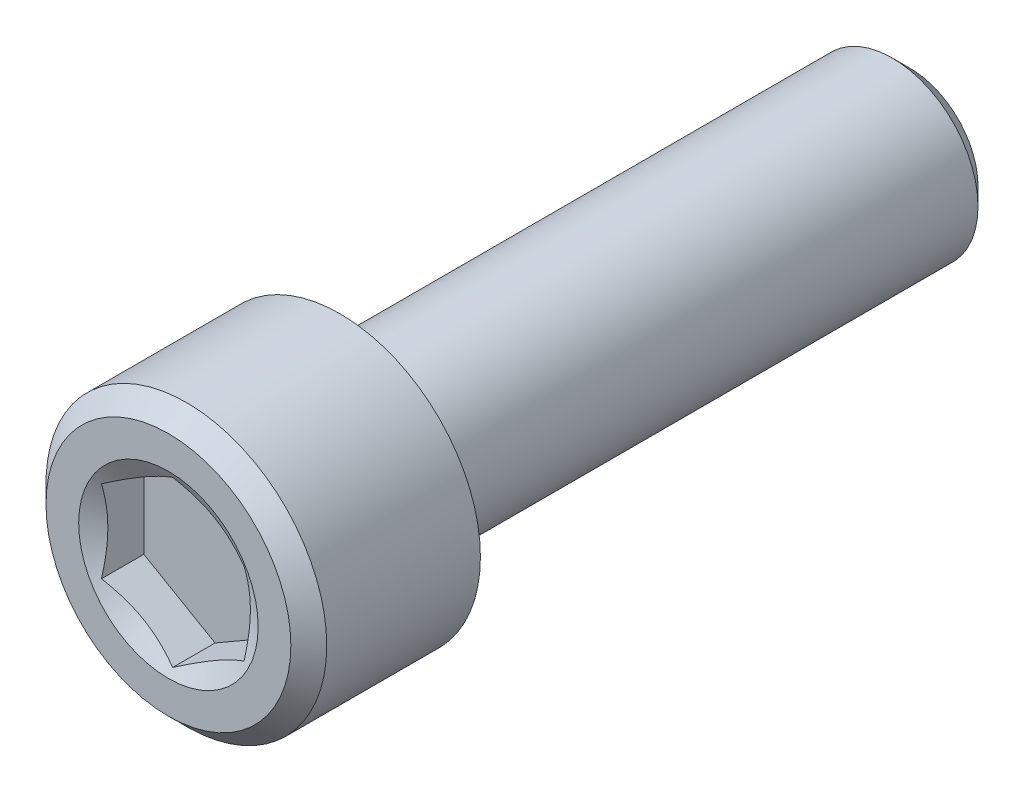
SolidWorks part; units mm, degrees
material "Galvanized Steel"
ref_plane "Top Plane" through (0, 0, 0) normal (0, 0, 1) x (1, 0, 0)
ref_plane "Front Plane" through (0, 0, 0) normal (0, 1, 0) x (1, 0, 0)
ref_plane "Right Plane" through (0, 0, 0) normal (1, 0, 0) x (0, 0, -1)
sketch "Ske1" plane through (0, 0, 0) normal (0, 0, 1) x (1, 0, 0)
  circle A0 centre (0, 0) radius 3.91
  dimension "Head_Dia" = 7.82
extrude "Base1" add sketch "Ske1" along normal blind 4.78
sketch "BodySke" plane through (0, 0, 0) normal (1, 0, 0) x (0, 0, -1)
  line L0 (-1.3858, 0) -> (15.88, 0) construction
  line L1 (0, -3.91) -> (0, 3.91) construction
  line L3 (-4.78, 0) -> (0, 0) construction
  line L4 (15.88, 2.39) -> (-4.78, 2.39)
  line L7 (-4.78, 3.91) -> (-4.78, -3.91) construction
  line L8 (-4.78, 2.39) -> (-4.78, 0)
  line L9 (-4.78, 0) -> (15.88, 0)
  line L10 (15.88, 0) -> (15.88, 2.39)
  line L11 (-4.78, 0) -> (9.169, 0) construction
  line L12 (0.5, 0) -> (0.5, 5.6548) construction
  line L13 (7.88, 0) -> (7.88, 5.6548) construction
  dimension "Diameter" = 4.78
  dimension "Advance" = 0.5
  dimension "Thread_nom" = 8
  dimension "Length" = 15.88
revolve "BaseBody" add sketch "BodySke" angle 360 about L0
cosmetic thread "ThreadCosmetic" parameters "Thread_length"=8, "Thread_minor"=2.439
sketch "Ske8" plane through (0, 0, 4.78) normal (0, 0, 1) x (1, 0, 0)
  line L1 (0, 2.2921) -> (-1.985, 1.146)
  line L2 (-1.985, 1.146) -> (-1.985, -1.146)
  line L3 (-1.985, -1.146) -> (0, -2.2921)
  line L4 (0, -2.2921) -> (1.985, -1.146)
  line L5 (1.985, -1.146) -> (1.985, 1.146)
  line L6 (1.985, 1.146) -> (0, 2.2921)
  circle A0 centre (0, 0) radius 1.985 construction
  dimension "Width_Flats" = 3.97
extrude "Hex" cut sketch "Ske8" against normal blind 1.3
sketch "Ske9" plane through (0, 0, 4.78) normal (0, 0, 1) x (1, 0, 0)
  circle A1 centre (0, 0) radius 2.5
  dimension "Head_Fillet" = 5
extrude "Chamfer" cut sketch "Ske9" against normal blind 1.3 draft 60
chamfer "Chamfer1" distance 0.5 angle 45 2 edges at (2.39, 0, -15.88) (3.91, 0, 4.78)
equation "\"Thread_length@ThreadCosmetic\" = ((sgn( (\"Length@BodySke\" - \"Advance@BodySke\" * 2.0 ) - \"Thread_nom@BodySke\" )-1)*( (\"Length@BodySke\" - \"Advance@BodySke\"  * 2.0) - \"Thread_nom@BodySke\" ))/-2+ \"Thread_nom@BodySke\""
